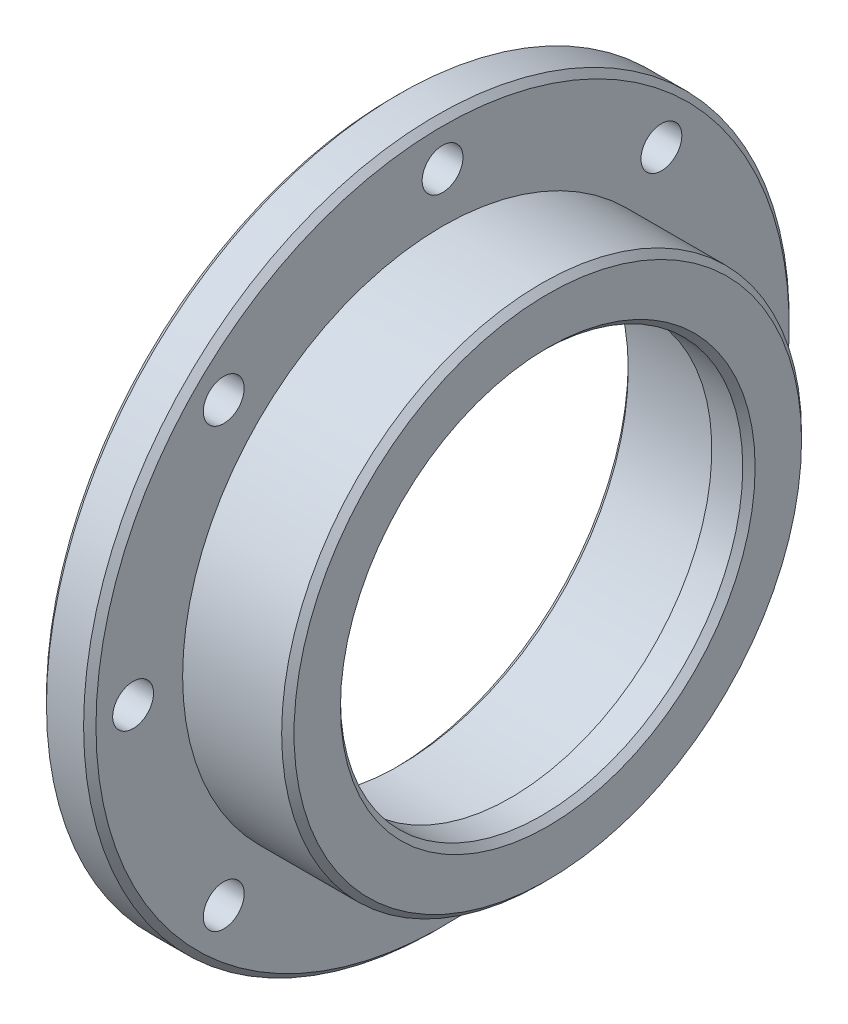
SolidWorks part; units mm, degrees
material "6061 合金"
ref_plane "前视基准面" through (0, 0, 0) normal (0, 0, 1) x (1, 0, 0)
ref_plane "上视基准面" through (0, 0, 0) normal (0, 1, 0) x (1, 0, 0)
ref_plane "右视基准面" through (0, 0, 0) normal (1, 0, 0) x (0, 0, -1)
other "Configuration Table"
sketch "草图1" plane through (0, 0, 0) normal (0, 0, 1) x (1, 0, 0)
  line L0 (0, 0) -> (28834.1059, 0) construction
  line L9 (0, 21) -> (0, 28.5)
  line L10 (0, 21) -> (4, 21)
  line L11 (0, 28.5) -> (4, 28.5)
  line L12 (4, 21) -> (4, 28.5)
  line L13 (0, 21) -> (9.5, 21)
  line L14 (0, 21) -> (0, 18.5)
  line L15 (9.5, 21) -> (9.5, 18.5)
  line L16 (0, 18.5) -> (9.5, 18.5)
  line L17 (9.5, 21) -> (12.5, 21)
  line L18 (9.5, 21) -> (9.5, 16.25)
  line L19 (12.5, 21) -> (12.5, 16.25)
  line L20 (9.5, 16.25) -> (12.5, 16.25)
  line L21 (4, 22) -> (4, 50022) construction
  line L22 (8, 39.7938) -> (8, -49960.2062) construction
  line L23 (6, 35.2795) -> (6, -49964.7205) construction
  dimension "D1" = 4
  dimension "D2" = 37
  dimension "D3" = 32.5
  dimension "D4" = 57
  dimension "D5" = 3.5
  dimension "D6" = 4
  dimension "D7" = 2
  dimension "D8" = 9.5
  dimension "D9" = 42
  dimension "D10" = 3
revolve "旋转1" add sketch "草图1" angle 360 about L0
chamfer "倒角1" distance 0.5 angle 45 5 edges at (12.5, 0, 21) (12.5, 0, 16.25) (0, 0, 28.5) (4, 0, 28.5) (0, 0, 18.5)
hole_wizard "M4 螺纹孔1" positions "草图2" profile "草图3" tap size "M4" standard "GB" end condition through all
sketch "草图2" plane through (4, 0, 0) normal (1, 0, 0) x (0, 0, -1)
  point P0 (0, 25)
  dimension "D1" = 25
sketch "草图3" plane through (4, 25, 0) normal (0, 1, 0) x (0, 0, -1)
  line L0 (0, 0) -> (0, 4)
  line L1 (0, 4) -> (1.65, 4)
  line L2 (1.65, 4) -> (1.65, 0)
  line L5 (1.65, 0) -> (0, 0)
  line L11 (0, -6.35) -> (0, 107.95) construction
  dimension "通孔螺纹孔钻头直径" = 3.3
  dimension "通孔螺纹孔钻头深度" = 4
cosmetic thread "孔螺蚊线1" parameters "D2"=4
pattern_circular "阵列(圆周)1" count 8 over 360 about axis through (0, 0, 0) along (1, 0, 0) of "M4 螺纹孔1"
